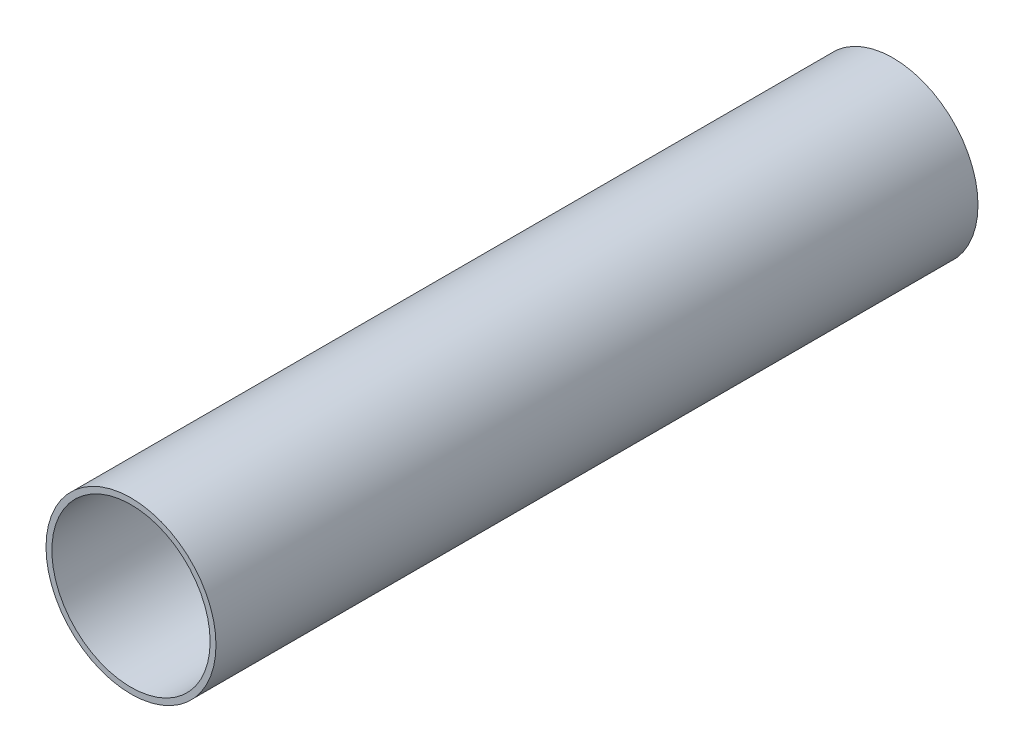
SolidWorks part; units mm, degrees
ref_plane "Front Plane" through (0, 0, 0) normal (0, 0, 1) x (1, 0, 0)
ref_plane "Top Plane" through (0, 0, 0) normal (0, 1, 0) x (1, 0, 0)
ref_plane "Right Plane" through (0, 0, 0) normal (1, 0, 0) x (0, 0, -1)
sketch "Sketch1" plane through (0, 0, 0) normal (0, 0, 1) x (1, 0, 0)
  circle A0 centre (0, 0) radius 27
  circle A1 centre (0, 0) radius 29
  dimension "D1" = 54
  dimension "D2" = 2
extrude "Boss-Extrude1" add sketch "Sketch1" along normal blind 260
